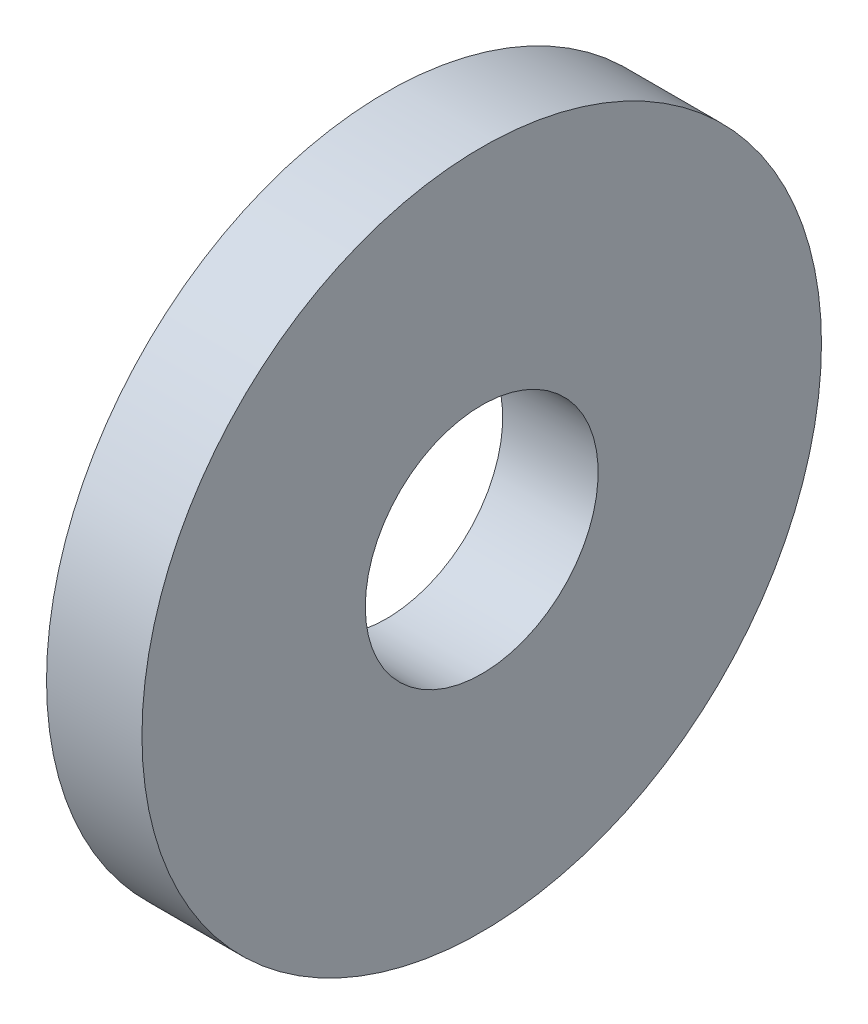
SolidWorks part; units mm, degrees
ref_plane "Front Plane" through (0, 0, 0) normal (0, 0, 1) x (1, 0, 0)
ref_plane "Top Plane" through (0, 0, 0) normal (0, 1, 0) x (1, 0, 0)
ref_plane "Right Plane" through (0, 0, 0) normal (1, 0, 0) x (0, 0, -1)
sketch "Sketch1" plane through (0, 0, 0) normal (0, 0, 1) x (1, 0, 0)
  line L0 (0, 3.05) -> (0, 8.9)
  line L1 (0, 8.9) -> (-2.5, 8.9)
  line L2 (-2.5, 8.9) -> (-2.5, 3.05)
  line L3 (-2.5, 3.05) -> (0, 3.05)
  line L4 (-10, 0) -> (1000, 0) construction
revolve "Revolve1" add sketch "Sketch1" angle 360 about L4
